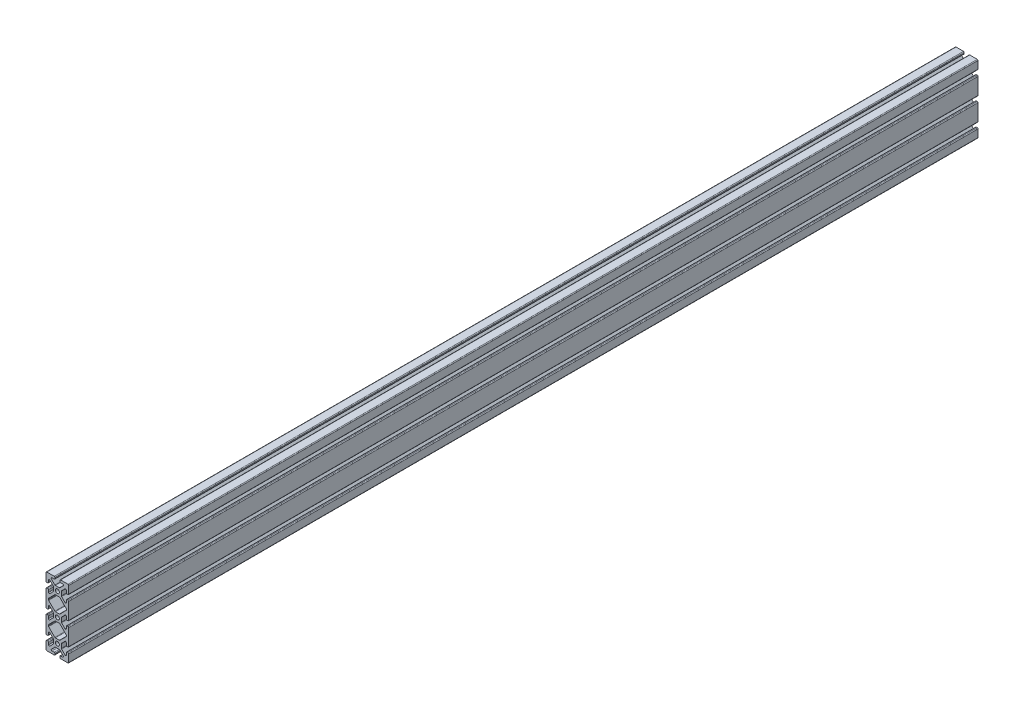
SolidWorks part; units mm, degrees
material "6061 Alloy"
ref_plane "Front Plane" through (0, 0, 0) normal (0, 0, 1) x (1, 0, 0)
ref_plane "Top Plane" through (0, 0, 0) normal (0, 1, 0) x (1, 0, 0)
ref_plane "Right Plane" through (0, 0, 0) normal (1, 0, 0) x (0, 0, -1)
sketch "Sketch1" plane through (0, 0, 0) normal (0, 0, 1) x (1, 0, 0)
  line L0 (0, 0) -> (0, 50000) construction
  line L1 (-19.05, 19.05) -> (19.05, 19.05) construction
  line L2 (-19.05, 19.05) -> (-19.05, -19.05) construction
  line L3 (-19.05, -19.05) -> (19.05, -19.05) construction
  line L4 (19.05, 19.05) -> (19.05, -19.05) construction
  line L5 (-19.05, 19.05) -> (19.05, -19.05) construction
  line L6 (-19.05, -19.05) -> (19.05, 19.05) construction
  line L7 (0, 0) -> (50000, 0) construction
  line L8 (-12.1123, 14.986) -> (-3.8827, 6.7564)
  line L9 (-19.05, 19.05) -> (-4.064, 19.05)
  line L10 (-4.064, 19.05) -> (-4.064, 14.986)
  line L11 (-4.064, 14.986) -> (-12.1123, 14.986)
  line L12 (-3.8827, 6.7564) -> (3.8827, 6.7564)
  line L13 (-6.7564, 3.8827) -> (-6.7564, -3.8827)
  line L14 (-14.986, 12.1123) -> (-6.7564, 3.8827)
  line L15 (-14.986, 4.064) -> (-14.986, 12.1123)
  line L16 (-19.05, 4.064) -> (-14.986, 4.064)
  line L17 (-19.05, 19.05) -> (-19.05, 4.064)
  line L18 (19.05, 4.064) -> (14.986, 4.064)
  line L19 (19.05, 19.05) -> (19.05, 4.064)
  line L20 (14.986, 4.064) -> (14.986, 12.1123)
  line L21 (14.986, 12.1123) -> (6.7564, 3.8827)
  line L22 (6.7564, 3.8827) -> (6.7564, -3.8827)
  line L23 (12.1123, 14.986) -> (3.8827, 6.7564)
  line L24 (4.064, 14.986) -> (12.1123, 14.986)
  line L25 (4.064, 19.05) -> (4.064, 14.986)
  line L26 (19.05, 19.05) -> (4.064, 19.05)
  line L27 (14.986, -12.1123) -> (6.7564, -3.8827)
  line L28 (14.986, -4.064) -> (14.986, -12.1123)
  line L29 (19.05, -4.064) -> (14.986, -4.064)
  line L30 (19.05, -34.036) -> (19.05, -4.064)
  line L31 (-19.05, -34.036) -> (-14.986, -34.036)
  line L32 (-3.8827, -6.7564) -> (-14.986, -17.8597)
  line L33 (-14.986, -34.036) -> (-14.986, -25.9877)
  line L34 (3.8827, -6.7564) -> (14.986, -17.8597)
  line L35 (-3.8827, -6.7564) -> (3.8827, -6.7564)
  line L36 (-14.986, -25.9877) -> (-6.7564, -34.2173)
  line L37 (-3.8827, -31.3436) -> (3.8827, -31.3436)
  line L38 (3.8827, -31.3436) -> (14.986, -20.2403)
  line L39 (-3.8827, -31.3436) -> (-14.986, -20.2403)
  line L40 (-14.986, -12.1123) -> (-6.7564, -3.8827)
  line L41 (-14.986, -4.064) -> (-14.986, -12.1123)
  line L42 (-19.05, -4.064) -> (-14.986, -4.064)
  line L43 (-19.05, -34.036) -> (-19.05, -4.064)
  line L44 (19.05, -34.036) -> (14.986, -34.036)
  line L45 (14.986, -34.036) -> (14.986, -25.9877)
  line L46 (14.986, -25.9877) -> (6.7564, -34.2173)
  line L47 (14.986, -58.3403) -> (14.986, -55.9597)
  line L48 (-14.986, -58.3403) -> (-14.986, -55.9597)
  line L49 (14.986, -50.2123) -> (6.7564, -41.9827)
  line L50 (14.986, -42.164) -> (14.986, -50.2123)
  line L51 (6.7564, -41.9827) -> (6.7564, -34.2173)
  line L52 (19.05, -42.164) -> (14.986, -42.164)
  line L53 (-19.05, -42.164) -> (-19.05, -72.136)
  line L54 (-19.05, -72.136) -> (-14.986, -72.136)
  line L55 (-14.986, -72.136) -> (-14.986, -64.0877)
  line L56 (-14.986, -64.0877) -> (-6.7564, -72.3173)
  line L57 (-3.8827, -44.8564) -> (-14.986, -55.9597)
  line L58 (3.8827, -44.8564) -> (14.986, -55.9597)
  line L59 (-3.8827, -44.8564) -> (3.8827, -44.8564)
  line L60 (-6.7564, -41.9827) -> (-6.7564, -34.2173)
  line L61 (-14.986, -50.2123) -> (-6.7564, -41.9827)
  line L62 (-3.8827, -69.4436) -> (3.8827, -69.4436)
  line L63 (3.8827, -69.4436) -> (14.986, -58.3403)
  line L64 (-14.986, -42.164) -> (-14.986, -50.2123)
  line L65 (-3.8827, -69.4436) -> (-14.986, -58.3403)
  line L66 (-14.986, -17.8597) -> (-14.986, -20.2403)
  line L67 (14.986, -17.8597) -> (14.986, -20.2403)
  line L68 (0, -38.1) -> (-50000, -38.1) construction
  line L69 (-19.05, -42.164) -> (-14.986, -42.164)
  line L70 (19.05, -42.164) -> (19.05, -72.136)
  line L71 (19.05, -72.136) -> (14.986, -72.136)
  line L72 (14.986, -72.136) -> (14.986, -64.0877)
  line L73 (14.986, -64.0877) -> (6.7564, -72.3173)
  line L74 (19.05, -95.25) -> (4.064, -95.25)
  line L75 (4.064, -95.25) -> (4.064, -91.186)
  line L76 (4.064, -91.186) -> (12.1123, -91.186)
  line L77 (12.1123, -91.186) -> (3.8827, -82.9564)
  line L78 (6.7564, -80.0827) -> (6.7564, -72.3173)
  line L79 (14.986, -88.3123) -> (6.7564, -80.0827)
  line L80 (14.986, -80.264) -> (14.986, -88.3123)
  line L81 (19.05, -95.25) -> (19.05, -80.264)
  line L82 (19.05, -80.264) -> (14.986, -80.264)
  line L83 (-19.05, -95.25) -> (-19.05, -80.264)
  line L84 (-19.05, -80.264) -> (-14.986, -80.264)
  line L85 (-14.986, -80.264) -> (-14.986, -88.3123)
  line L86 (-14.986, -88.3123) -> (-6.7564, -80.0827)
  line L87 (-6.7564, -80.0827) -> (-6.7564, -72.3173)
  line L88 (-3.8827, -82.9564) -> (3.8827, -82.9564)
  line L89 (-4.064, -91.186) -> (-12.1123, -91.186)
  line L90 (-4.064, -95.25) -> (-4.064, -91.186)
  line L91 (-19.05, -95.25) -> (-4.064, -95.25)
  line L92 (-12.1123, -91.186) -> (-3.8827, -82.9564)
  circle A0 centre (0, 0) radius 3.3274
  circle A1 centre (0, -38.1) radius 3.3274
  circle A2 centre (0, -76.2) radius 3.3274
  point P0 (0, 0)
  point P28 (0, 6.7564)
  point P32 (6.7564, 0)
  point P44 (-6.7564, 0)
  point P64 (-6.7564, -38.1)
  point P65 (6.7564, -38.1)
  point P74 (-6.7564, -38.1)
  point P75 (6.7564, -38.1)
  point P107 (-6.7564, -76.2)
  point P108 (6.7564, -76.2)
  point P109 (0, -82.9564)
  dimension "D3" = 14.986
  dimension "D2" = 6.6548
  dimension "D1" = 38.1
  dimension "D4" = 4.064
  dimension "D5" = 2.032
  dimension "D6" = 12.2936
extrude "Boss-Extrude1" add sketch "Sketch1" along normal blind 1524
fillet "Fillet1" radius 1.27 84 edges at (-14.986, -34.036, 762) (-19.05, -34.036, 762) (-6.7564, -34.2173, 762) (6.7564, -34.2173, 762) (14.986, -25.9877, 762) (14.986, -34.036, 762) (19.05, -34.036, 762) (-19.05, 4.064, 762) (-14.986, 4.064, 762) (-14.986, 12.1123, 762) (-6.7564, 3.8827, 762) (-6.7564, -3.8827, 762) (-19.05, -4.064, 762) (-14.986, -4.064, 762) (-14.986, -12.1123, 762) (3.8827, -31.3436, 762) (-3.8827, -31.3436, 762) (-3.8827, -6.7564, 762) (3.8827, -6.7564, 762) (14.986, -12.1123, 762) (19.05, -4.064, 762) (14.986, -4.064, 762) (6.7564, -3.8827, 762) (6.7564, 3.8827, 762) (14.986, 4.064, 762) (19.05, 4.064, 762) (14.986, 12.1123, 762) (19.05, 19.05, 762) (4.064, 19.05, 762) (4.064, 14.986, 762) (12.1123, 14.986, 762) (3.8827, 6.7564, 762) (-3.8827, 6.7564, 762) (-12.1123, 14.986, 762) (-4.064, 14.986, 762) (-4.064, 19.05, 762) (-19.05, 19.05, 762) (14.986, -20.2403, 762) (14.986, -17.8597, 762) (-14.986, -20.2403, 762) (-14.986, -17.8597, 762) (-14.986, -88.3123, 762) (-19.05, -95.25, 762) (-4.064, -95.25, 762) (-4.064, -91.186, 762) (-12.1123, -91.186, 762) (-3.8827, -82.9564, 762) (3.8827, -82.9564, 762) (12.1123, -91.186, 762) (4.064, -91.186, 762) (4.064, -95.25, 762) (19.05, -95.25, 762) (19.05, -80.264, 762) (14.986, -80.264, 762) (14.986, -88.3123, 762) (-19.05, -72.136, 762) (-14.986, -72.136, 762) (14.986, -72.136, 762) (19.05, -72.136, 762) (-19.05, -80.264, 762) (-14.986, -80.264, 762) (-6.7564, -80.0827, 762) (6.7564, -80.0827, 762) (-6.7564, -72.3173, 762) (6.7564, -72.3173, 762) (3.8827, -69.4436, 762) (-3.8827, -69.4436, 762) (3.8827, -44.8564, 762) (-3.8827, -44.8564, 762) (-14.986, -64.0877, 762) (14.986, -64.0877, 762) (14.986, -58.3403, 762) (14.986, -55.9597, 762) (-14.986, -58.3403, 762) (-14.986, -55.9597, 762) (-19.05, -42.164, 762) (-14.986, -42.164, 762) (14.986, -50.2123, 762) (-14.986, -50.2123, 762) (19.05, -42.164, 762) (14.986, -42.164, 762) (6.7564, -41.9827, 762) (-6.7564, -41.9827, 762) (-14.986, -25.9877, 762)
